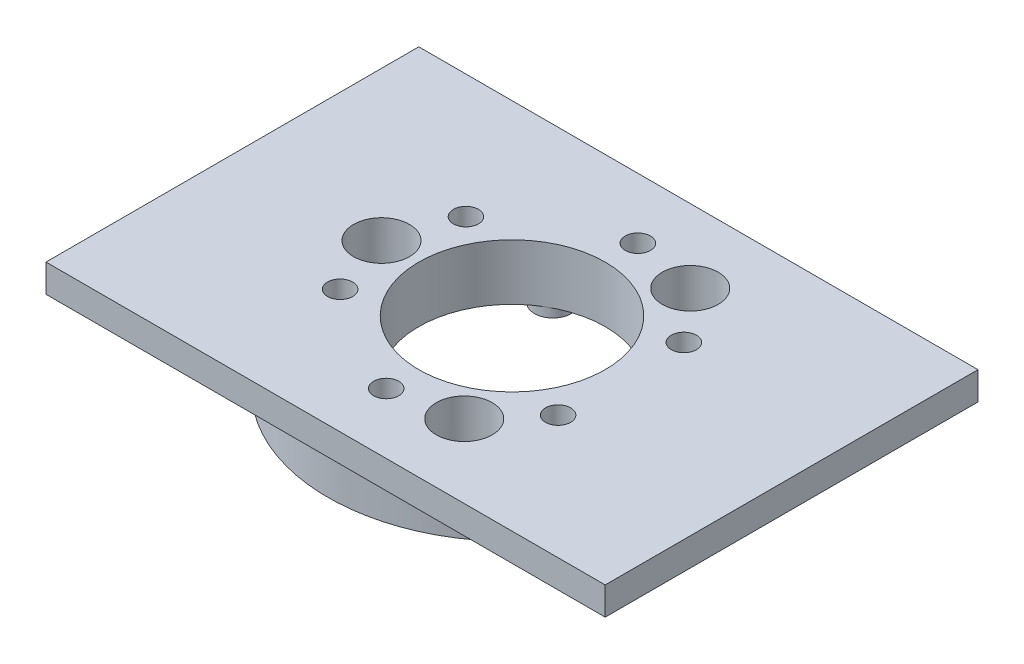
SolidWorks part; units mm, degrees
material "ABS"
ref_plane "前视基准面" through (0, 0, 0) normal (0, 0, 1) x (1, 0, 0)
ref_plane "上视基准面" through (0, 0, 0) normal (0, 1, 0) x (1, 0, 0)
ref_plane "右视基准面" through (0, 0, 0) normal (1, 0, 0) x (0, 0, -1)
other "Configuration Table"
sketch "草图1" plane through (0, 0, 0) normal (0, 1, 0) x (1, 0, 0)
  circle A0 centre (0, 0) radius 18.77
  circle A1 centre (0, 0) radius 19.75
  dimension "D1" = 37.54
  dimension "D2" = 39.5
extrude "凸台-拉伸1" add sketch "草图1" along normal blind 1
sketch "草图2" plane through (0, 1, 0) normal (0, 1, 0) x (1, 0, 0)
  circle A0 centre (0, 0) radius 19.75 construction
  circle A1 centre (0, 0) radius 19.75
extrude "凸台-拉伸2" add sketch "草图2" along normal blind 6
sketch "草图5" plane through (0, 1, 0) normal (0, -1, 0) x (1, 0, 0)
  line L0 (0, 0) -> (0, 13.5) construction
  circle A0 centre (0, 0) radius 13.5 construction
  circle A1 centre (0, 13.5) radius 1.35
  circle A2 centre (11.6913, 6.75) radius 1.35
  circle A3 centre (11.6913, -6.75) radius 1.35
  circle A4 centre (0, -13.5) radius 1.35
  circle A5 centre (-11.6913, -6.75) radius 1.35
  circle A6 centre (-11.6913, 6.75) radius 1.35
  circle A7 centre (0, 0) radius 10
  dimension "D1" = 27
  dimension "D2" = 2.7
  dimension "D5" = 20
  dimension "D4" = 13.5
  dimension "D3" = 6
extrude "切除-拉伸2" cut sketch "草图5" against normal through all
sketch "草图6" plane through (0, 1, 0) normal (0, -1, 0) x (1, 0, 0)
  line L0 (0, 0) -> (12, 0) construction
  circle A0 centre (0, 0) radius 12 construction
  circle A1 centre (12, 0) radius 1.98
  circle A2 centre (-6, -10.3923) radius 1.98
  circle A3 centre (-6, 10.3923) radius 1.98
  dimension "D1" = 24
  dimension "D2" = 3.96
  dimension "D4" = 12
  dimension "D3" = 3
extrude "凸台-拉伸4" add sketch "草图6" along normal blind 1
sketch "草图7" plane through (0, 1, 0) normal (0, -1, 0) x (1, 0, 0)
  line L0 (0, 0) -> (-14, 0) construction
  circle A0 centre (0, 0) radius 14 construction
  circle A1 centre (-14, 0) radius 3
  circle A2 centre (7, 12.1244) radius 3
  circle A3 centre (7, -12.1244) radius 3
  dimension "D1" = 28
  dimension "D2" = 6
  dimension "D4" = 14
  dimension "D3" = 3
sketch "草图11" plane through (0, 7, 0) normal (0, 1, 0) x (1, 0, 0)
  line L1 (-30, -20) -> (30, -20)
  line L6 (-30, -20) -> (-30, 20)
  line L7 (-30, 20) -> (30, 20)
  line L8 (30, -20) -> (30, 20)
  line L9 (-30, -20) -> (30, 20) construction
  line L10 (-30, 20) -> (30, -20) construction
  circle A7 centre (0, 0) radius 19.75
  circle A11 centre (0, 0) radius 19.75
  dimension "D2" = 40
  dimension "D3" = 60
  dimension "D1" = 0
extrude "凸台-拉伸6" add sketch "草图11" against normal blind 3
extrude "切除-拉伸7" cut sketch "草图7" against normal blind 20
sketch "草图12" plane through (0, 1, 0) normal (0, -1, 0) x (1, 0, 0)
  line L0 (0, 0) -> (-3.5, -6.0622) construction
  line L1 (0, 0) -> (-6, -10.3923) construction
  line L2 (0.2026, 0.3509) -> (-0.6702, -20.6309) construction
  arc A0 (-6.4387, -19.5713) -> (5.1664, -20.054) centre (0.2026, 0.3509) ccw
  dimension "D1" = 21
sketch "草图15" plane through (0, 1, 0) normal (0, -1, 0) x (-1, 0, 0)
  line L0 (0, 0) -> (0, 13.5) construction
  line L1 (-5.5189, 18.5418) -> (-5.9908, 20.1273)
  line L2 (-5.9908, 20.1273) -> (0, 0) construction
  line L3 (0, 0) -> (5.9908, 20.1273) construction
  line L4 (5.5189, 18.5418) -> (5.9908, 20.1273)
  arc A0 (5.9908, 20.1273) -> (-5.9908, 20.1273) centre (0, 0) ccw
  arc A1 (5.5189, 18.5418) -> (-5.5189, 18.5418) centre (0, 0) ccw
  point P5 (0, 21)
  dimension "D1" = 21
extrude "凸台-拉伸7" add sketch "草图15" along normal up to surface (1 mm away) and the other way blind 2 up to face at (0, 0, 19.75)
